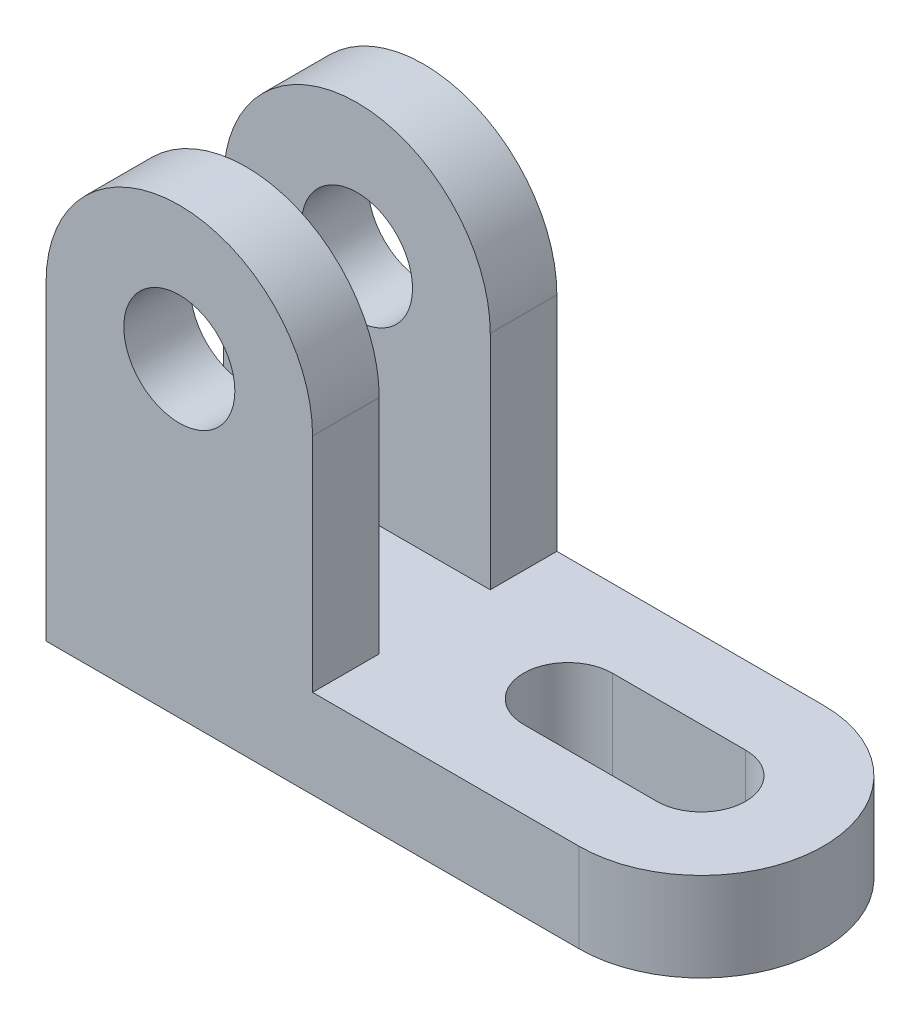
SolidWorks part; units mm, degrees
ref_plane "Front Plane" through (0, 0, 0) normal (0, 0, 1) x (1, 0, 0)
ref_plane "Top Plane" through (0, 0, 0) normal (0, 1, 0) x (1, 0, 0)
ref_plane "Right Plane" through (0, 0, 0) normal (1, 0, 0) x (0, 0, -1)
sketch "Sketch1" plane through (0, 0, 0) normal (0, 1, 0) x (1, 0, 0)
  line L1 (-59, 22) -> (59, 22)
  line L2 (-59, 22) -> (-59, -22)
  line L3 (-59, -22) -> (59, -22)
  line L4 (59, 22) -> (59, -22)
  line L5 (-59, 22) -> (59, -22) construction
  line L6 (-59, -22) -> (59, 22) construction
  circle A0 centre (37, 0) radius 22
  point P0 (0, 0)
  dimension "D1" = 118
  dimension "D2" = 44
extrude "Boss-Extrude1" add sketch "Sketch1" along normal blind 16 contours A0 L1 L2 L3 | A0
sketch "Sketch5" plane through (0, 16, 0) normal (0, 1, 0) x (1, 0, 0)
  line L0 (37, 0) -> (13, 0) construction
  line L1 (37, -8) -> (13, -8)
  line L2 (37, 8) -> (13, 8)
  arc A0 (37, -8) -> (37, 8) centre (37, 0) ccw
  arc A1 (13, 8) -> (13, -8) centre (13, 0) ccw
  point P4 (25, 0)
  dimension "D1" = 24
  dimension "D2" = 16
extrude "Cut-Extrude2" cut sketch "Sketch5" against normal blind 16
sketch "Sketch6" plane through (0, 0, 22) normal (0, 0, 1) x (1, 0, 0)
  line L1 (-59, 16) -> (-11, 16)
  line L2 (-59, 16) -> (-59, 56)
  line L3 (-59, 56) -> (-11, 56)
  line L4 (-11, 16) -> (-11, 56)
  circle A0 centre (-35, 56) radius 24
  circle A1 centre (-35, 56) radius 10
  line M3 (37, 16) -> (-59, 16)
  dimension "D3" = 20
  dimension "D1" = 40
  dimension "D2" = 48
extrude "Boss-Extrude2" add sketch "Sketch6" against normal blind 12 contours A0 L2 L4 M3 | A1 L3 A0 | A1 L3 A0
mirror "Mirror1" about plane through (0, 0, 0) normal (0, 0, 1) of "Boss-Extrude2"
